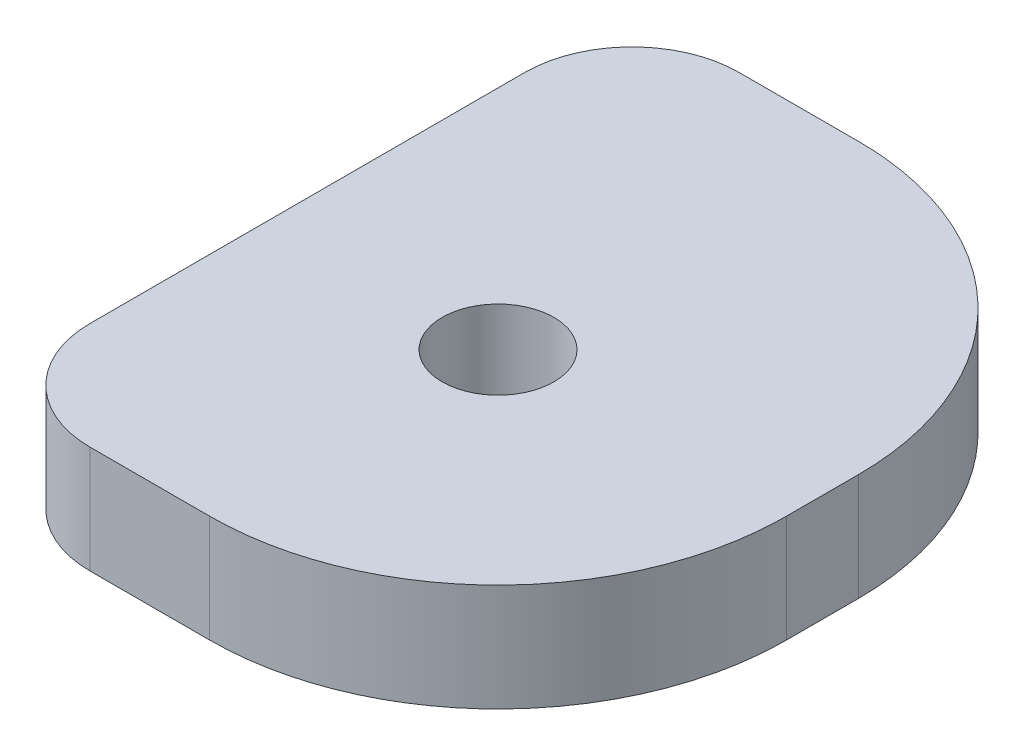
SolidWorks part; units mm, degrees
ref_plane "Front Plane" through (0, 0, 0) normal (0, 0, 1) x (1, 0, 0)
ref_plane "Top Plane" through (0, 0, 0) normal (0, 1, 0) x (1, 0, 0)
ref_plane "Right Plane" through (0, 0, 0) normal (1, 0, 0) x (0, 0, -1)
sketch "Sketch1" plane through (0, 0, 0) normal (0, 1, 0) x (1, 0, 0)
  line L1 (-25.4, 11.43) -> (25.4, 11.43)
  line L2 (-25.4, 11.43) -> (-25.4, -11.43)
  line L3 (-25.4, -11.43) -> (25.4, -11.43)
  line L4 (25.4, 11.43) -> (25.4, -11.43)
  dimension "D1" = 22.86
  dimension "D2" = 50.8
  dimension "D3" = 11.43
  dimension "D4" = 25.4
extrude "Boss-Extrude1" add sketch "Sketch1" along normal blind 3.175
fillet "Fillet1" radius 10.16 2 edges at (-25.4, 1.5875, 11.43) (25.4, 1.5875, 11.43)
sketch "Sketch3" plane through (0, 3.175, 0) normal (0, 1, 0) x (1, 0, 0)
  line L0 (-7.7526, -1.27) -> (18.5521, -1.27) construction
  circle A0 centre (15.24, -1.27) radius 1.9685
  arc A2 (15.24, -11.43) -> (25.4, -1.27) centre (15.24, -1.27) ccw construction
  circle A3 centre (-3.81, -1.27) radius 1.9685
  dimension "D1" = 3.937
  dimension "D6" = 3.937
  dimension "D5" = 19.05
extrude "Cut-Extrude1" cut sketch "Sketch3" against normal through all
fillet "Fillet3" radius 10.16 2 edges at (-25.4, 1.5875, -11.43) (25.4, 1.5875, -11.43)
scale "Scale1" scale about centroid uniform scaling no x scale factor 0.84 y scale factor 1 z scale factor 0.84
sketch "Sketch4" plane through (0, 0, 0) normal (0, -1, 0) x (-1, 0, 0)
  line L0 (-6.0748, -9.5965) -> (-6.0748, 9.6059)
  line L1 (12.8228, -9.5965) -> (-12.7804, -9.5965) construction
  line L2 (-12.7804, 9.6059) -> (12.8228, 9.6059) construction
  line L3 (-21.3148, -1.0621) -> (-21.3148, 1.0715) construction
  line L4 (21.3572, 1.0715) -> (21.3572, -1.0621) construction
  line L5 (-6.0748, -9.5965) -> (21.3572, -9.5965)
  line L7 (-6.0748, 9.6059) -> (21.3572, 9.6059)
  line L8 (21.3572, -9.5965) -> (21.3572, 9.6059)
  dimension "D1" = 15.24
extrude "Cut-Extrude2" cut sketch "Sketch4" against normal through all contours L0 L7 L8 L5
fillet "Fillet4" radius 3.175 2 edges at (6.0748, 1.5875, 9.5965) (6.0748, 1.5875, -9.6059)
equation "\"D4@Sketch1\"=\"D2@Sketch1\"/2"
equation "\"D3@Sketch1\"=\"D1@Sketch1\"/2"
